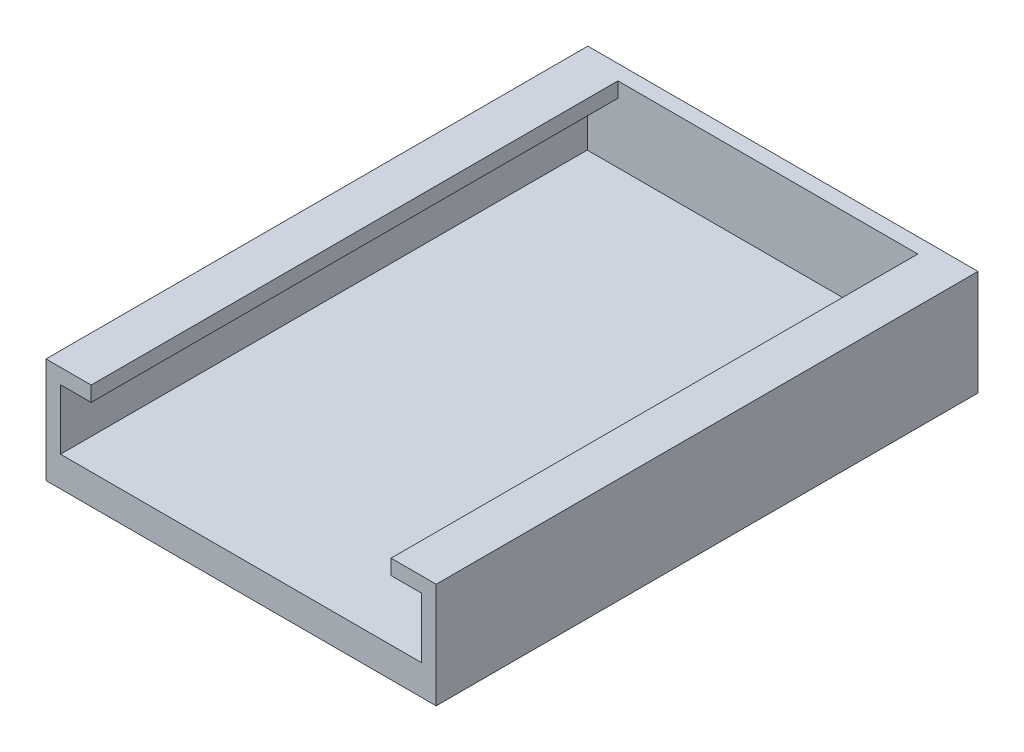
SolidWorks part; units mm, degrees
ref_plane "前视基准面" through (0, 0, 0) normal (0, 0, 1) x (1, 0, 0)
ref_plane "上视基准面" through (0, 0, 0) normal (0, 1, 0) x (1, 0, 0)
ref_plane "右视基准面" through (0, 0, 0) normal (1, 0, 0) x (0, 0, -1)
other "Configuration Table"
sketch "草图2" plane through (0, 0, 0) normal (0, 0, 1) x (1, 0, 0)
  line L0 (-10, 0) -> (10, 0)
  line L2 (10, 2) -> (12, 2)
  line L3 (12, 2) -> (12, 6)
  line L4 (12, 6) -> (9.9628, 6)
  line L5 (9.9628, 6) -> (9.9628, 7)
  line L6 (9.9628, 7) -> (12.9628, 7)
  line L7 (12.9628, 7) -> (12.9628, 0)
  line L8 (12.9628, 0) -> (10, 0)
  line L9 (0, 0) -> (0, 2.4523) construction
  line L10 (-12.9628, 0) -> (-10, 0)
  line L12 (-10, 2) -> (-12, 2)
  line L13 (-12, 2) -> (-12, 6)
  line L14 (-12.9628, 7) -> (-12.9628, 0)
  line L15 (-12, 6) -> (-9.9628, 6)
  line L16 (-9.9628, 7) -> (-12.9628, 7)
  line L17 (-9.9628, 6) -> (-9.9628, 7)
  line L18 (-10, 2) -> (10, 2)
  dimension "D1" = 10
  dimension "D2" = 2
  dimension "D3" = 3
  dimension "D4" = 4
  dimension "D5" = 2
  dimension "D6" = 1
extrude "凸台-拉伸2" add sketch "草图2" along normal blind 35
sketch "草图3" plane through (0, 0, 0) normal (0, 0, -1) x (-1, 0, 0)
  line L1 (-12.9628, 7) -> (12.9628, 7)
  line L2 (-12.9628, 7) -> (-12.9628, 0)
  line L3 (-12.9628, 0) -> (12.9628, 0)
  line L4 (12.9628, 7) -> (12.9628, 0)
extrude "凸台-拉伸3" add sketch "草图3" along normal blind 1
